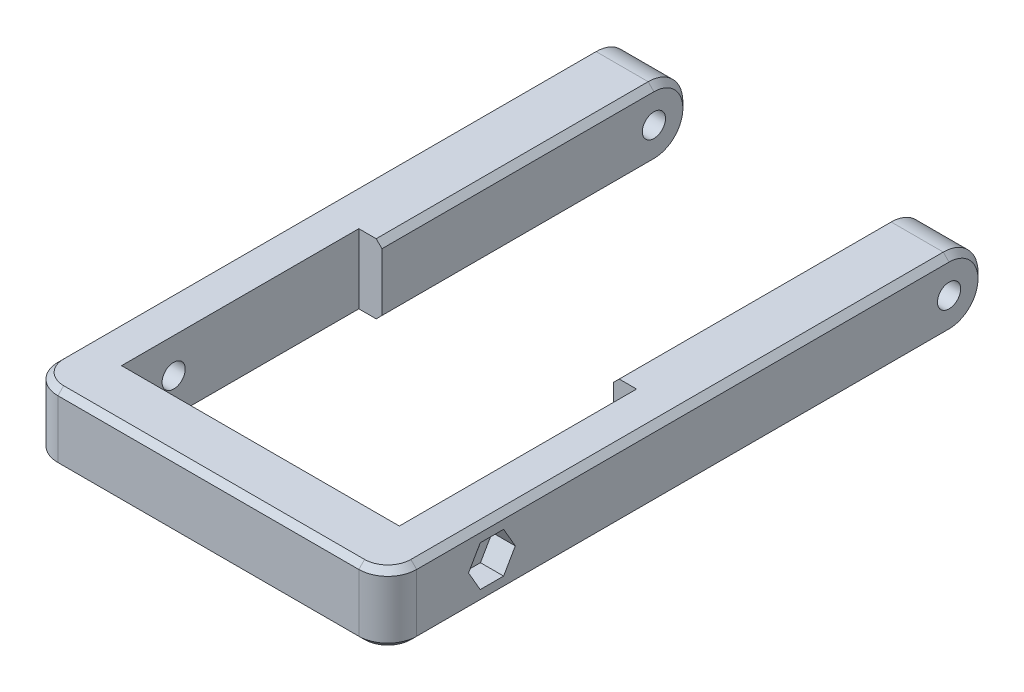
SolidWorks part; units mm, degrees
material "3D printed plastic"
ref_plane "Front Plane" through (0, 0, 0) normal (0, 0, 1) x (1, 0, 0)
ref_plane "Top Plane" through (0, 0, 0) normal (0, 1, 0) x (1, 0, 0)
ref_plane "Right Plane" through (0, 0, 0) normal (1, 0, 0) x (0, 0, -1)
sketch "Sketch1" plane through (0, 0, 0) normal (0, 1, 0) x (1, 0, 0)
  line L0 (20, 103) -> (31, 103)
  line L1 (-31, 0) -> (31, 0)
  line L2 (-31, 0) -> (-31, 103)
  line L3 (-31, 103) -> (-20, 103)
  line L4 (31, 0) -> (31, 103)
  line L6 (20, 103) -> (20, 10)
  line L7 (20, 10) -> (-20, 10)
  line L8 (-20, 103) -> (-20, 10)
  dimension "D1" = 62
  dimension "D2" = 11
  dimension "D3" = 10
  dimension "D4" = 93
extrude "Boss-Extrude1" add sketch "Sketch1" along normal mid plane 12
sketch "Sketch2" plane through (31, 0, 0) normal (1, 0, 0) x (0, 0, -1)
  line L1 (97, 0) -> (103, 0) construction
  line L2 (103, 6) -> (103, -6) construction
  line L3 (0, 6) -> (103, 6) construction
  line L4 (97, 6) -> (104, 6)
  line L5 (104, 6) -> (104, -6)
  line L6 (104, -6) -> (97, -6)
  line L7 (97, 0) -> (97, 6) construction
  circle A0 centre (97, 0) radius 2
  arc A1 (97, -6) -> (97, 6) centre (97, 0) ccw
  dimension "D1" = 4
  dimension "D3" = 1
extrude "Cut-Extrude1" cut sketch "Sketch2" against normal through all
sketch "Sketch3" plane through (31, 0, 0) normal (1, 0, 0) x (0, 0, -1)
  line L0 (18, 0) -> (97, 0) construction
  circle A0 centre (18, 0) radius 2
  circle A1 centre (97, 0) radius 2 construction
  dimension "D1" = 79
  dimension "D2" = 4
extrude "Cut-Extrude2" cut sketch "Sketch3" against normal through all
sketch "Sketch4" plane through (31, 0, 0) normal (1, 0, 0) x (0, 0, -1)
  line L1 (22.0415, 0) -> (20.0207, 3.5)
  line L2 (20.0207, 3.5) -> (15.9793, 3.5)
  line L3 (15.9793, 3.5) -> (13.9585, 0)
  line L4 (13.9585, 0) -> (15.9793, -3.5)
  line L5 (15.9793, -3.5) -> (20.0207, -3.5)
  line L6 (20.0207, -3.5) -> (22.0415, 0)
  circle A0 centre (18, 0) radius 3.5 construction
  dimension "D1" = 7
extrude "Cut-Extrude3" cut sketch "Sketch4" against normal blind 4
mirror "Mirror1" about plane through (0, 0, 0) normal (1, 0, 0) of "Cut-Extrude3"
sketch "Sketch6" plane through (0, 6, 0) normal (0, 1, 0) x (1, 0, 0)
  line L0 (20, 10) -> (-20, 10) construction
  line L1 (-24, 10) -> (24, 10)
  line L2 (-24, 10) -> (-24, 50)
  line L3 (-24, 50) -> (24, 50)
  line L4 (24, 10) -> (24, 50)
  line L5 (-20, 10) -> (-20, 97) construction
  line L6 (0, 10) -> (0, 0) construction
  dimension "D1" = 4
  dimension "D2" = 40
extrude "Cut-Extrude4" cut sketch "Sketch6" against normal through all
fillet "Fillet1" radius 5 2 edges at (-31, 0, 0) (31, 0, 0)
chamfer "Chamfer1" distance 1 angle 45 20 edges at (-20, 6, -73.5) (-20, 0, -103) (-20, -6, -73.5) (20, 6, -73.5) (20, 0, -103) (20, -6, -73.5) (0, 6, 0) (-29.5355, 6, -1.4645) (29.5355, 6, -1.4645) (-31, 6, -51) (31, 6, -51) (-31, 0, -103) (31, 0, -103) (-31, -6, -51) (31, -6, -51) (-29.5355, -6, -1.4645) (29.5355, -6, -1.4645) (0, -6, 0) (0, 6, -10) (0, -6, -10)
